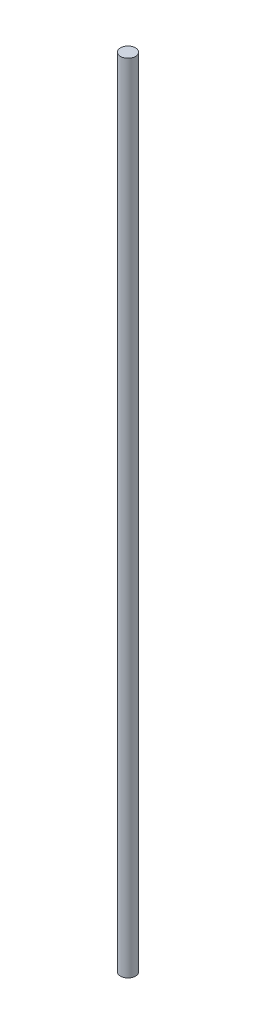
SolidWorks part; units mm, degrees
material "6061 合金"
ref_plane "前视基准面" through (0, 0, 0) normal (0, 0, 1) x (1, 0, 0)
ref_plane "上视基准面" through (0, 0, 0) normal (0, 1, 0) x (1, 0, 0)
ref_plane "右视基准面" through (0, 0, 0) normal (1, 0, 0) x (0, 0, -1)
other "Configuration Table"
sketch "草图1" plane through (0, 0, 0) normal (0, 1, 0) x (1, 0, 0)
  circle A0 centre (0, 0) radius 1.6
extrude "凸台-拉伸1" add sketch "草图1" along normal blind 170 contours A0
